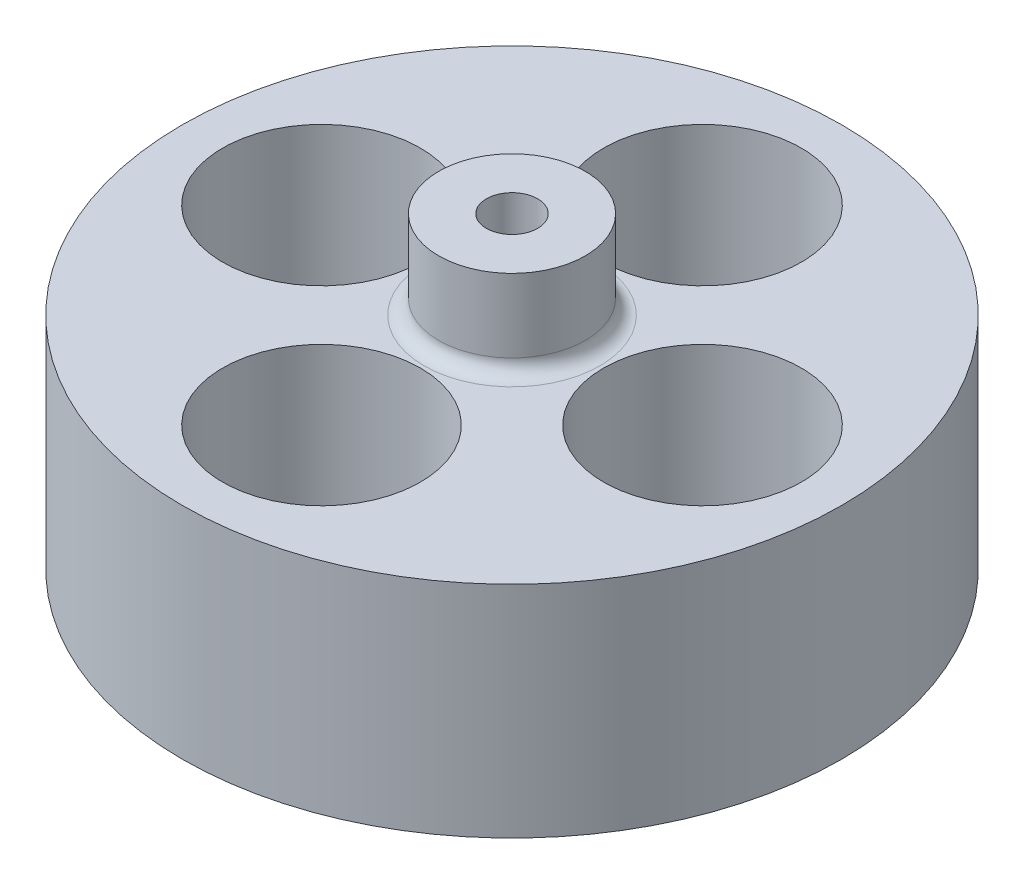
SolidWorks part; units mm, degrees
material "6061 Alloy"
ref_plane "Front Plane" through (0, 0, 0) normal (0, 0, 1) x (1, 0, 0)
ref_plane "Top Plane" through (0, 0, 0) normal (0, 1, 0) x (1, 0, 0)
ref_plane "Right Plane" through (0, 0, 0) normal (1, 0, 0) x (0, 0, -1)
sketch "Sketch1" plane through (0, 0, 0) normal (0, 1, 0) x (1, 0, 0)
  circle A0 centre (0, 0) radius 22.5
  dimension "D1" = 45
extrude "Boss-Extrude1" add sketch "Sketch1" along normal blind 15
sketch "Sketch2" plane through (0, 15, 0) normal (0, 1, 0) x (1, 0, 0)
  line L0 (0, -14.3) -> (0, 14.3) construction
  line L1 (-14.3, 0) -> (14.3, 0) construction
  line L2 (0, 19.75) -> (16.0728, 19.75) construction
  line L3 (0, 22.5) -> (15.4299, 22.5) construction
  circle A0 centre (0, 13) radius 6.75
  circle A1 centre (0, 0) radius 22.5 construction
  dimension "D1" = 13.5
  dimension "D2" = 13
  dimension "D3" = 2.75
extrude "Cut-Extrude1" cut sketch "Sketch2" against normal blind 10
sketch "Sketch3" plane through (0, 5, 0) normal (0, 1, 0) x (1, 0, 0)
  circle A0 centre (0, 13) radius 2
  dimension "D1" = 4
extrude "Cut-Extrude2" cut sketch "Sketch3" against normal blind 35
pattern_circular "CirPattern1" count 4 over 360 about axis through (0, 0, 0) along (0, 1, 0) of "Cut-Extrude1", "Cut-Extrude2"
sketch "Sketch6" plane through (0, 15, 0) normal (0, 1, 0) x (1, 0, 0)
  circle A0 centre (0, 0) radius 1.75
  dimension "D2" = 3.5
extrude "Cut-Extrude4" cut sketch "Sketch6" against normal blind 45
sketch "Sketch7" plane through (0, 15, 0) normal (0, 1, 0) x (1, 0, 0)
  circle A0 centre (0, 0) radius 5
  circle A1 centre (0, 0) radius 1.75
  dimension "D1" = 10
extrude "Boss-Extrude2" add sketch "Sketch7" along normal blind 6
fillet "Fillet1" radius 1 1 edges at (0, 15, 5)
sketch "Sketch8" plane through (0, 0, 0) normal (0, -1, 0) x (1, 0, 0)
  circle A0 centre (0, 0) radius 3.5
  dimension "D1" = 7
extrude "Cut-Extrude5" cut sketch "Sketch8" against normal blind 5
